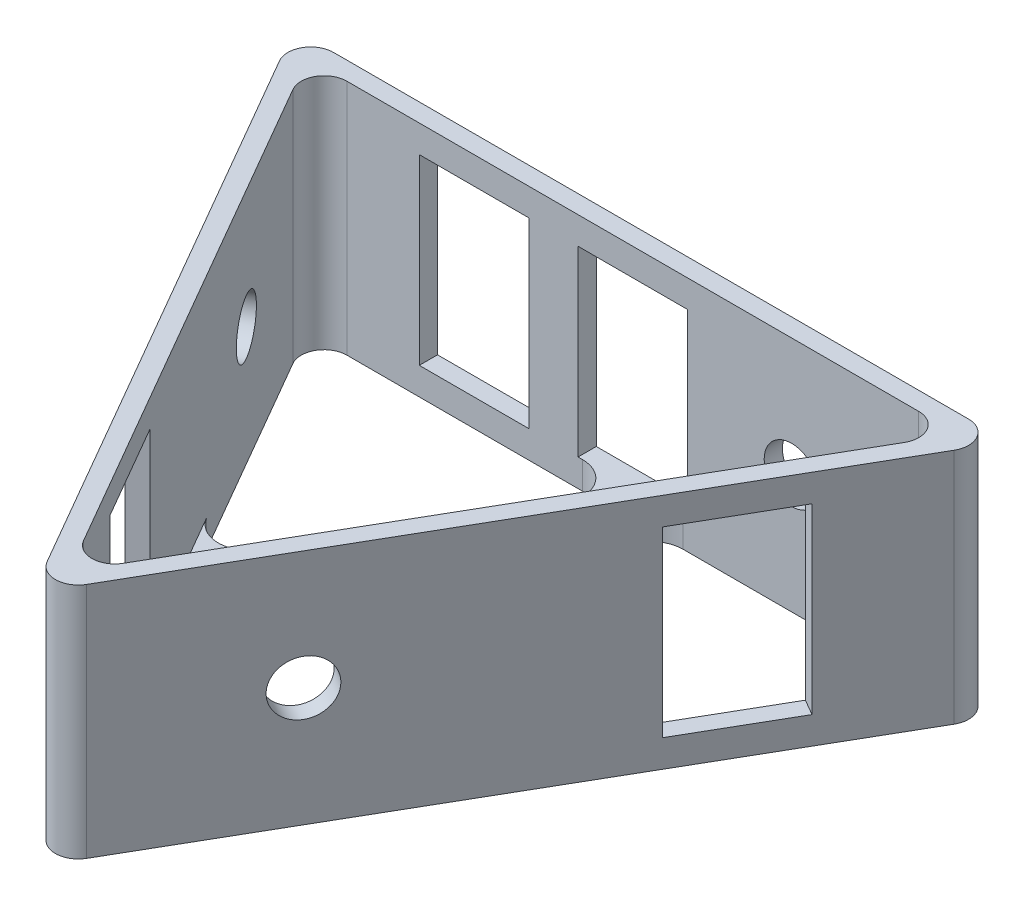
SolidWorks part; units mm, degrees
ref_plane "Front Plane" through (0, 0, 0) normal (0, 0, 1) x (1, 0, 0)
ref_plane "Top Plane" through (0, 0, 0) normal (0, 1, 0) x (1, 0, 0)
ref_plane "Right Plane" through (0, 0, 0) normal (1, 0, 0) x (0, 0, -1)
sketch "Sketch1" plane through (0, 0, 0) normal (0, 1, 0) x (1, 0, 0)
  line L0 (-55.0808, 36.1982) -> (23.1679, 36.1982)
  line L1 (23.1679, 36.1982) -> (-15.9564, -31.5672)
  line L2 (-55.0808, 36.1982) -> (-15.9564, -31.5672)
  line L3 (-51.6167, 34.1982) -> (19.7038, 34.1982)
  line L4 (19.7038, 34.1982) -> (-15.9564, -27.5672)
  line L5 (-51.6167, 34.1982) -> (-15.9564, -27.5672)
  dimension "D1" = 2
extrude "Boss-Extrude1" add sketch "Sketch1" along normal blind 26
fillet "Fillet1" radius 2.5 6 edges at (-15.9564, 13, 27.5672) (-15.9564, 13, 31.5672) (23.1679, 13, -36.1982) (19.7038, 13, -34.1982) (-51.6167, 13, -34.1982) (-55.0808, 13, -36.1982)
sketch "Sketch2" plane through (-25.6363, 0, 14.8011) normal (-0.866, 0, 0.5) x (0.5, 0, 0.866)
  line L0 (-54.5588, 26) -> (15.0296, 0)
  line L1 (15.0296, 26) -> (-54.5588, 0)
  line L2 (-19.7646, 13) -> (15.0296, 13)
  line L7 (15.0296, 0) -> (15.0296, 26) construction
  line L8 (-19.7646, 13) -> (-54.5588, 13)
  line L9 (-8.3675, 3) -> (3.6325, 3)
  line L10 (-8.3675, 3) -> (-8.3675, 23)
  line L11 (-8.3675, 23) -> (3.6325, 23)
  line L12 (3.6325, 3) -> (3.6325, 23)
  line L13 (-8.3675, 3) -> (3.6325, 23) construction
  line L14 (-8.3675, 23) -> (3.6325, 3) construction
  line L15 (-54.5588, 26) -> (-54.5588, 0) construction
  circle A0 centre (-37.1617, 13) radius 3
  point P8 (-19.7646, 13)
  point P13 (-2.3675, 13)
  dimension "D1" = 12
  dimension "D2" = 20
extrude "Cut-Extrude1" cut sketch "Sketch2" against normal up to next contours L9 L12 L0 L10 | L0 L12 L2 L10 | L2 L12 L1 L10 | L1 L12 L11 L10 | A0
sketch "Sketch3" plane through (1.7017, 0, 0.9824) normal (0.866, 0, 0.5) x (0.5, 0, -0.866)
  line L0 (-30.9861, 26) -> (38.6024, 0)
  line L1 (38.6024, 26) -> (-30.9861, 0)
  line L2 (3.8082, 13) -> (38.6024, 13)
  line L7 (3.8082, 13) -> (-30.9861, 13)
  line L8 (15.2053, 3) -> (27.2053, 3)
  line L9 (38.6024, 0) -> (38.6024, 26) construction
  line L10 (15.2053, 3) -> (15.2053, 23)
  line L11 (15.2053, 23) -> (27.2053, 23)
  line L12 (27.2053, 3) -> (27.2053, 23)
  line L13 (15.2053, 3) -> (27.2053, 23) construction
  line L14 (15.2053, 23) -> (27.2053, 3) construction
  line L15 (-30.9861, 26) -> (-30.9861, 0) construction
  circle A0 centre (-13.5889, 13) radius 3
  point P8 (3.8082, 13)
  point P9 (21.2053, 13)
  dimension "D1" = 12
  dimension "D2" = 20
extrude "Cut-Extrude2" cut sketch "Sketch3" against normal up to next contours L0 L12 L2 L10 | L8 L12 L0 L10 | L2 L12 L1 L10 | L1 L12 L11 L10 | A0
sketch "Sketch4" plane through (0, 0, -36.1982) normal (0, 0, -1) x (-1, 0, 0)
  line L0 (-18.8378, 26) -> (50.7507, 0)
  line L1 (50.7507, 26) -> (-18.8378, 0)
  line L2 (15.9564, 13) -> (50.7507, 13)
  line L3 (9.9564, 3) -> (21.9564, 3)
  line L4 (9.9564, 3) -> (9.9564, 23)
  line L5 (9.9564, 23) -> (21.9564, 23)
  line L6 (21.9564, 3) -> (21.9564, 23)
  line L7 (9.9564, 3) -> (21.9564, 23) construction
  line L8 (9.9564, 23) -> (21.9564, 3) construction
  line L9 (50.7507, 0) -> (50.7507, 26) construction
  line L10 (15.9564, 13) -> (-18.8378, 13)
  line L11 (27.3536, 3) -> (39.3536, 3)
  line L12 (27.3536, 3) -> (27.3536, 23)
  line L13 (27.3536, 23) -> (39.3536, 23)
  line L14 (39.3536, 3) -> (39.3536, 23)
  line L15 (27.3536, 3) -> (39.3536, 23) construction
  line L16 (27.3536, 23) -> (39.3536, 3) construction
  line L17 (-18.8378, 26) -> (-18.8378, 0) construction
  circle A0 centre (-1.4407, 13) radius 3
  point P8 (15.9564, 13)
  point P17 (33.3536, 13)
  dimension "D1" = 12
  dimension "D2" = 20
  dimension "D3" = 12
  dimension "D4" = 20
extrude "Cut-Extrude3" cut sketch "Sketch4" against normal up to next contours L3 L6 L0 L1 L4 | L4 L1 L0 | L1 L6 L5 L4 L0 | L2 L6 L1 | L11 L14 L0 L12 | L0 L14 L2 L12 | L2 L14 L1 L12 | L1 L14 L13 L12 | A0
sketch "Sketch5" plane through (0, 0, 0) normal (0, -1, 0) x (1, 0, 0)
  line L1 (-49.4516, -30.4482) -> (-18.1215, 23.8172) construction
  line L2 (-13.7914, 23.8172) -> (17.5387, -30.4482) construction
  line L4 (15.3737, -34.1982) -> (-47.2866, -34.1982) construction
  line L6 (-33.7866, -3.3155) -> (-15.9564, -13.6097)
  line L7 (1.8737, -3.3155) -> (-15.9564, -13.6097)
  line L8 (-15.9564, -13.6097) -> (-15.9564, -34.1982)
  line L9 (-32.7866, -1.5835) -> (-15.9564, -11.3003)
  line L10 (2.8737, -5.0476) -> (-13.9564, -14.7644)
  line L11 (-13.9564, -14.7644) -> (-13.9564, -34.1982)
  line L12 (-34.7866, -5.0476) -> (-17.9564, -14.7644)
  line L13 (0.8737, -1.5835) -> (-15.9564, -11.3003)
  line L14 (-17.9564, -14.7644) -> (-17.9564, -34.1982)
  line L15 (-17.9564, -13.6097) -> (-17.9564, -34.1982) construction
  line L16 (-34.7866, -5.0476) -> (-16.9564, -15.3418) construction
  line L17 (2.8737, -5.0476) -> (-14.9564, -15.3418) construction
  line L18 (-13.9564, -13.6097) -> (-13.9564, -34.1982) construction
  line L19 (-32.7866, -1.5835) -> (-14.9564, -11.8777) construction
  line L20 (0.8737, -1.5835) -> (-16.9564, -11.8777) construction
  line L21 (-34.7866, -5.0476) -> (-32.7866, -1.5835)
  line L22 (0.8737, -1.5835) -> (2.8737, -5.0476)
  line L23 (-13.9564, -34.1982) -> (-17.9564, -34.1982)
  circle A0 centre (-15.9564, -13.6097) radius 1.25
  line M22 (-13.7914, 23.8172) -> (17.5387, -30.4482)
  line M24 (15.3737, -34.1982) -> (-47.2866, -34.1982)
  line M26 (-49.4516, -30.4482) -> (-18.1215, 23.8172)
  dimension "D1" = 2
  dimension "D2" = 2
extrude "Boss-Extrude2" add sketch "Sketch5" against normal blind 3 contours A0 L6 L12 L14 L8 M26 M24 | A0 L7 L13 L9 L6 M22 M26 | A0 L8 L11 L10 L7 M24 M22
fillet "Fillet2" radius 3.5 9 edges at (2.8737, 1.5, -5.0476) (-13.9564, 1.5, -34.1982) (-13.9564, 1.5, -14.7644) (-15.9564, 1.5, -11.3003) (0.8737, 1.5, -1.5835) (-32.7866, 1.5, -1.5835) (-17.9564, 1.5, -14.7644) (-34.7866, 1.5, -5.0476) (-17.9564, 1.5, -34.1982)
